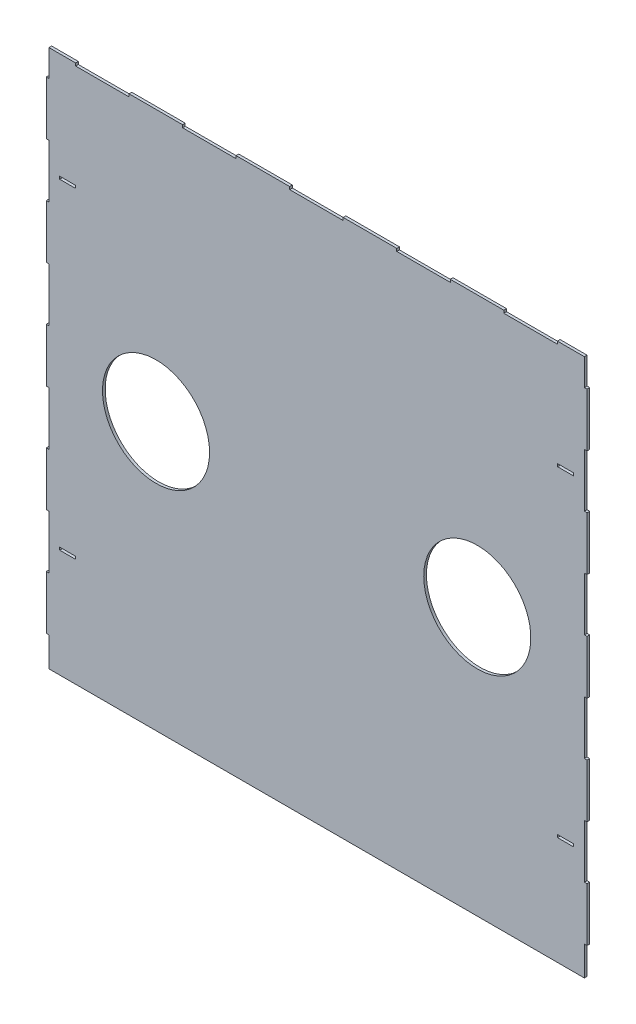
SolidWorks part; units mm, degrees
ref_plane "Front Plane" through (0, 0, 0) normal (0, 0, 1) x (1, 0, 0)
ref_plane "Top Plane" through (0, 0, 0) normal (0, 1, 0) x (1, 0, 0)
ref_plane "Right Plane" through (0, 0, 0) normal (1, 0, 0) x (0, 0, -1)
sketch "Sketch1" plane through (0, 0, 0) normal (0, 0, 1) x (1, 0, 0)
  line L0 (473.9726, -60.3425) -> (473.9726, -110.3425)
  line L1 (-1.0274, 12.1575) -> (48.7503, 12.1575)
  line L2 (-26.0274, 12.1575) -> (-26.0274, -10.3425)
  line L3 (-26.0274, -487.8425) -> (473.9726, -487.8425)
  line L4 (473.9726, 12.1575) -> (473.9726, -10.3425)
  line L5 (473.9726, -10.3425) -> (476.4726, -10.3425)
  line L6 (473.9726, -110.3425) -> (476.4726, -110.3425)
  line L7 (473.9726, -60.3425) -> (476.4726, -60.3425)
  line L8 (476.4726, -10.3425) -> (476.4726, -60.3425)
  line L9 (476.4726, -110.3425) -> (476.4726, -160.3425)
  line L10 (473.9726, -160.3425) -> (476.4726, -160.3425)
  line L11 (473.9726, -210.3425) -> (476.4726, -210.3425)
  line L12 (476.4726, -210.3425) -> (476.4726, -260.3425)
  line L13 (473.9726, -260.3425) -> (476.4726, -260.3425)
  line L14 (473.9726, -310.3425) -> (476.4726, -310.3425)
  line L15 (476.4726, -310.3425) -> (476.4726, -360.3425)
  line L16 (473.9726, -360.3425) -> (476.4726, -360.3425)
  line L17 (473.9726, -410.3425) -> (476.4726, -410.3425)
  line L18 (476.4726, -410.3425) -> (476.4726, -460.3425)
  line L19 (473.9726, -460.3425) -> (476.4726, -460.3425)
  line L20 (473.9726, -160.3425) -> (473.9726, -210.3425)
  line L21 (473.9726, -260.3425) -> (473.9726, -310.3425)
  line L22 (473.9726, -360.3425) -> (473.9726, -410.3425)
  line L23 (473.9726, -460.3425) -> (473.9726, -487.8425)
  line L24 (223.9726, 12.1575) -> (223.9726, -525.1857) construction
  line L25 (-26.0274, -10.3425) -> (-28.5274, -10.3425)
  line L26 (-26.0274, -60.3425) -> (-28.5274, -60.3425)
  line L27 (-28.5274, -10.3425) -> (-28.5274, -60.3425)
  line L28 (-26.0274, -110.3425) -> (-28.5274, -110.3425)
  line L29 (-26.0274, -160.3425) -> (-28.5274, -160.3425)
  line L30 (-28.5274, -110.3425) -> (-28.5274, -160.3425)
  line L31 (-26.0274, -210.3425) -> (-28.5274, -210.3425)
  line L32 (-26.0274, -260.3425) -> (-28.5274, -260.3425)
  line L33 (-28.5274, -210.3425) -> (-28.5274, -260.3425)
  line L34 (-26.0274, -310.3425) -> (-28.5274, -310.3425)
  line L35 (-28.5274, -310.3425) -> (-28.5274, -360.3425)
  line L36 (-26.0274, -360.3425) -> (-28.5274, -360.3425)
  line L37 (-26.0274, -410.3425) -> (-28.5274, -410.3425)
  line L38 (-26.0274, -460.3425) -> (-28.5274, -460.3425)
  line L39 (-28.5274, -410.3425) -> (-28.5274, -460.3425)
  line L40 (-26.0274, -60.3425) -> (-26.0274, -110.3425)
  line L41 (-26.0274, -160.3425) -> (-26.0274, -210.3425)
  line L42 (-26.0274, -260.3425) -> (-26.0274, -310.3425)
  line L43 (-26.0274, -360.3425) -> (-26.0274, -410.3425)
  line L44 (-26.0274, -460.3425) -> (-26.0274, -487.8425)
  line L45 (98.7503, 12.1575) -> (148.7503, 12.1575)
  line L46 (148.7503, 12.1575) -> (148.7503, 14.6575)
  line L47 (48.7503, 12.1575) -> (48.7503, 14.6575)
  line L48 (48.7503, 14.6575) -> (98.7503, 14.6575)
  line L49 (98.7503, 12.1575) -> (98.7503, 14.6575)
  line L50 (148.7503, 14.6575) -> (198.7503, 14.6575)
  line L51 (198.7503, 12.1575) -> (198.7503, 14.6575)
  line L52 (248.7503, 12.1575) -> (248.7503, 14.6575)
  line L53 (248.7503, 14.6575) -> (298.7503, 14.6575)
  line L54 (298.7503, 12.1575) -> (298.7503, 14.6575)
  line L55 (348.7503, 12.1575) -> (348.7503, 14.6575)
  line L56 (348.7503, 14.6575) -> (398.7503, 14.6575)
  line L57 (398.7503, 12.1575) -> (398.7503, 14.6575)
  line L58 (448.7503, 12.1575) -> (448.7503, 14.6575)
  line L59 (448.7503, 14.6575) -> (473.9726, 14.6575)
  line L60 (473.9726, 12.1575) -> (473.9726, 14.6575)
  line L61 (198.7503, 12.1575) -> (248.7503, 12.1575)
  line L62 (298.7503, 12.1575) -> (348.7503, 12.1575)
  line L63 (398.7503, 12.1575) -> (448.7503, 12.1575)
  line L64 (-74.3164, -237.8425) -> (605.7825, -237.8425) construction
  line L65 (23.9726, -173.5421) -> (23.9726, -287.8425) construction
  line L66 (-16.0274, -386.8425) -> (-16.0274, -384.3425)
  line L67 (498.7503, 12.1575) -> (498.7503, 14.6575) [skipped]
  line L68 (448.9726, -86.8425) -> (463.9726, -86.8425)
  line L69 (-1.0274, 12.1575) -> (-1.0274, 14.6575)
  line L70 (-1.0274, 14.6575) -> (-26.0274, 14.6575)
  line L71 (-26.0274, 12.1575) -> (-26.0274, 14.6575)
  line L72 (448.9726, -86.8425) -> (448.9726, -84.3425)
  line L73 (448.9726, -84.3425) -> (463.9726, -84.3425)
  line L74 (463.9726, -86.8425) -> (463.9726, -84.3425)
  line L75 (-1.0274, -384.3425) -> (-16.0274, -384.3425)
  line L76 (-1.0274, -386.8425) -> (-1.0274, -384.3425)
  line L77 (-1.0274, -386.8425) -> (-16.0274, -386.8425)
  line L78 (-16.0274, -86.8425) -> (-16.0274, -84.3425)
  line L79 (-1.0274, -84.3425) -> (-16.0274, -84.3425)
  line L80 (-1.0274, -86.8425) -> (-1.0274, -84.3425)
  line L81 (-1.0274, -86.8425) -> (-16.0274, -86.8425)
  line L82 (448.9726, -386.8425) -> (463.9726, -386.8425)
  line L83 (448.9726, -386.8425) -> (448.9726, -384.3425)
  line L84 (448.9726, -384.3425) -> (463.9726, -384.3425)
  line L85 (463.9726, -386.8425) -> (463.9726, -384.3425)
  line L86 (448.9726, -186.8425) -> (463.9726, -186.8425) [skipped]
  line L87 (448.9726, -186.8425) -> (448.9726, -184.3425) [skipped]
  line L88 (448.9726, -184.3425) -> (463.9726, -184.3425) [skipped]
  line L89 (463.9726, -186.8425) -> (463.9726, -184.3425) [skipped]
  line L90 (448.9726, -286.8425) -> (463.9726, -286.8425) [skipped]
  line L91 (448.9726, -286.8425) -> (448.9726, -284.3425) [skipped]
  line L92 (448.9726, -284.3425) -> (463.9726, -284.3425) [skipped]
  line L93 (463.9726, -286.8425) -> (463.9726, -284.3425) [skipped]
  circle A0 centre (73.9726, -237.8425) radius 50
  circle A1 centre (373.9726, -237.8425) radius 50
  dimension "D10" = 100
  dimension "D1" = 500
  dimension "D2" = 500
  dimension "D3" = 2.5
  dimension "D4" = 50
  dimension "D5" = 22.5
  dimension "D6" = 5
  dimension "D7" = 2.5
  dimension "D8" = 50
  dimension "D9" = 250
  dimension "D11" = 50
  dimension "D12" = 4
extrude "Boss-Extrude1" add sketch "Sketch1" along normal blind 2.5 contours L1 L47 L48 L49 L45 L46 L50 L51 L61 L52 L53 L54 L62 L55 L56 L57 L63 L58 L59 L60 L4 L5 L8 L7 L0 L6 L9 L10 L20 L11 L12 L13 L21 L14 L15 L16 L22 L17 L18 L19 L23 L3 L44 L38 L39 L37 L43 L36 L35 L34 L42 L32 L33 L31 L41 L29 L30 L28 L40 L26 L27 L25 L2
